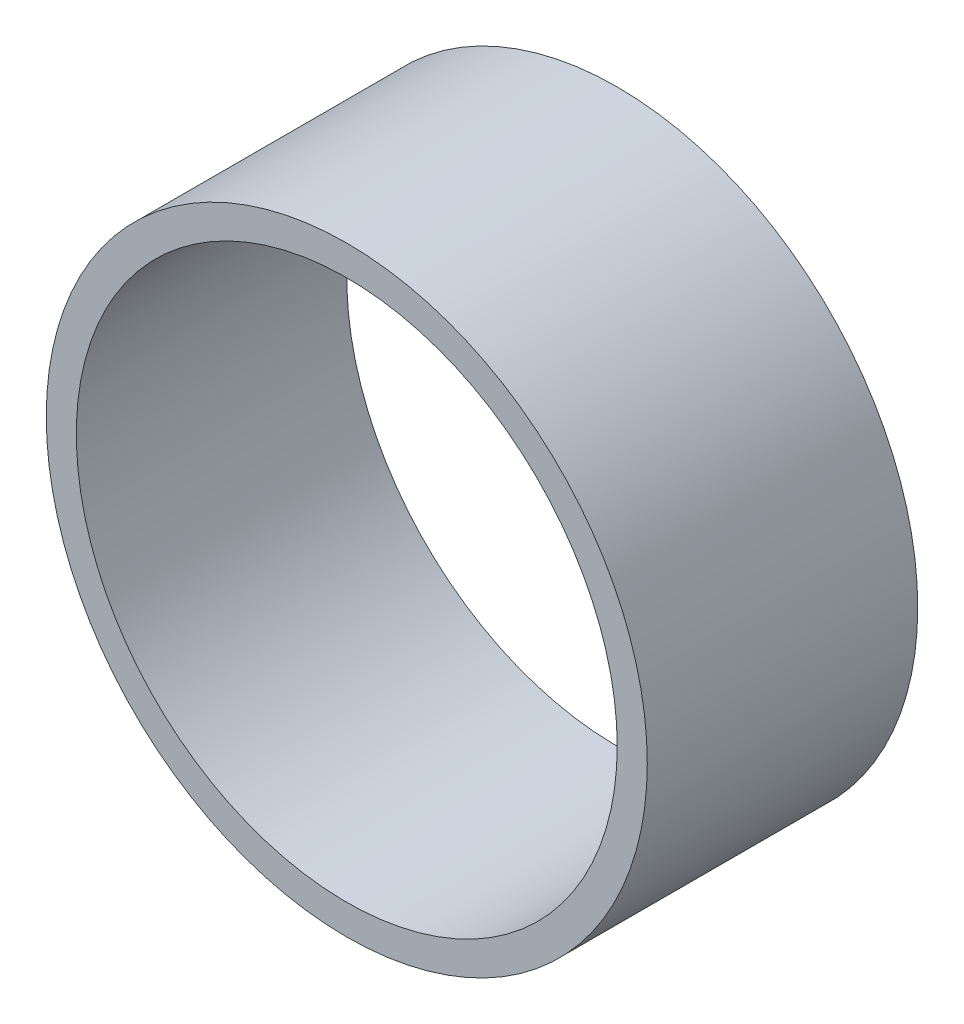
SolidWorks part; units mm, degrees
ref_plane "前视基准面" through (0, 0, 0) normal (0, 0, 1) x (1, 0, 0)
ref_plane "上视基准面" through (0, 0, 0) normal (0, 1, 0) x (1, 0, 0)
ref_plane "右视基准面" through (0, 0, 0) normal (1, 0, 0) x (0, 0, -1)
sketch "草图1" plane through (0, 0, 0) normal (0, 0, 1) x (1, 0, 0)
  circle A0 centre (0, 0) radius 10
  dimension "D1" = 20
extrude "凸台-拉伸1" add sketch "草图1" along normal blind 9
scale "缩放比例2" scale about origin uniform scaling yes scale factor 1.2
shell "抽壳3" thickness 1.2
